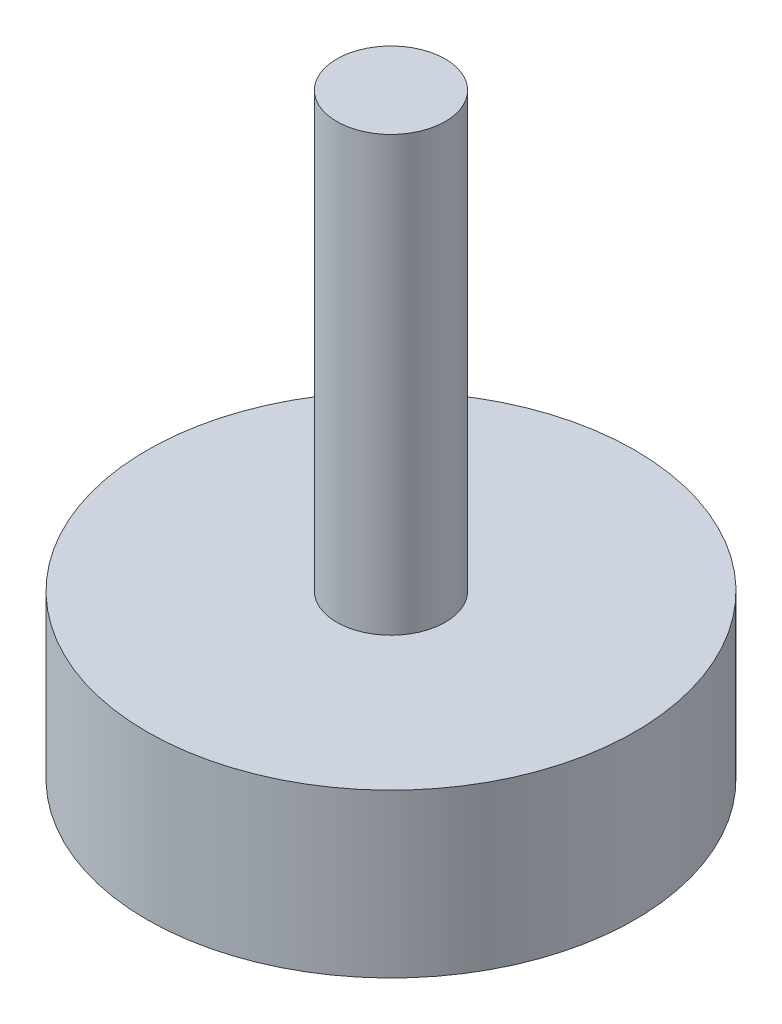
SolidWorks part; units mm, degrees
material "Chrome Stainless Steel"
ref_plane "Front" through (0, 0, 0) normal (0, 0, 1) x (1, 0, 0)
ref_plane "Top" through (0, 0, 0) normal (0, 1, 0) x (1, 0, 0)
ref_plane "Right" through (0, 0, 0) normal (1, 0, 0) x (0, 0, -1)
sketch "Sketch1" plane through (0, 0, 0) normal (0, 0, 1) x (1, 0, 0)
  line L0 (-14.2875, 0) -> (14.2875, 0) construction
  line L1 (0, 9.525) -> (0, 34.925)
  line L2 (-14.2875, 0) -> (-14.2875, 9.525) construction
  line L3 (-14.2875, 9.525) -> (14.2875, 9.525) construction
  line L4 (14.2875, 9.525) -> (14.2875, 0) construction
  line L5 (-3.175, 34.925) -> (3.175, 34.925) construction
  line L6 (3.175, 34.925) -> (3.175, 9.525)
  line L7 (-3.175, 34.925) -> (-3.175, 9.525) construction
  line L8 (0, 34.925) -> (3.175, 34.925)
  line L9 (0, 9.525) -> (3.175, 9.525)
  dimension "Base Dia (B)" = 28.575
  dimension "Thread Lg (A)" = 25.4
  dimension "Overall Ht (C)" = 34.925
  dimension "Thread Major Dia" = 6.35
revolve "Revolve1" add sketch "Sketch1" angle 360 mid plane about L1
sketch "Sketch5" plane through (0, 0, 0) normal (0, 0, 1) x (1, 0, 0)
  line L0 (0, 0) -> (0, 9.525)
  line L1 (-14.2875, 0) -> (14.2875, 0) construction
  line L3 (0, 9.525) -> (14.2875, 9.525)
  line L4 (14.2875, 0) -> (0, 0)
  line L5 (14.2875, 9.525) -> (14.2875, 0)
revolve "Revolve2" add sketch "Sketch5" angle 360 mid plane about L0
